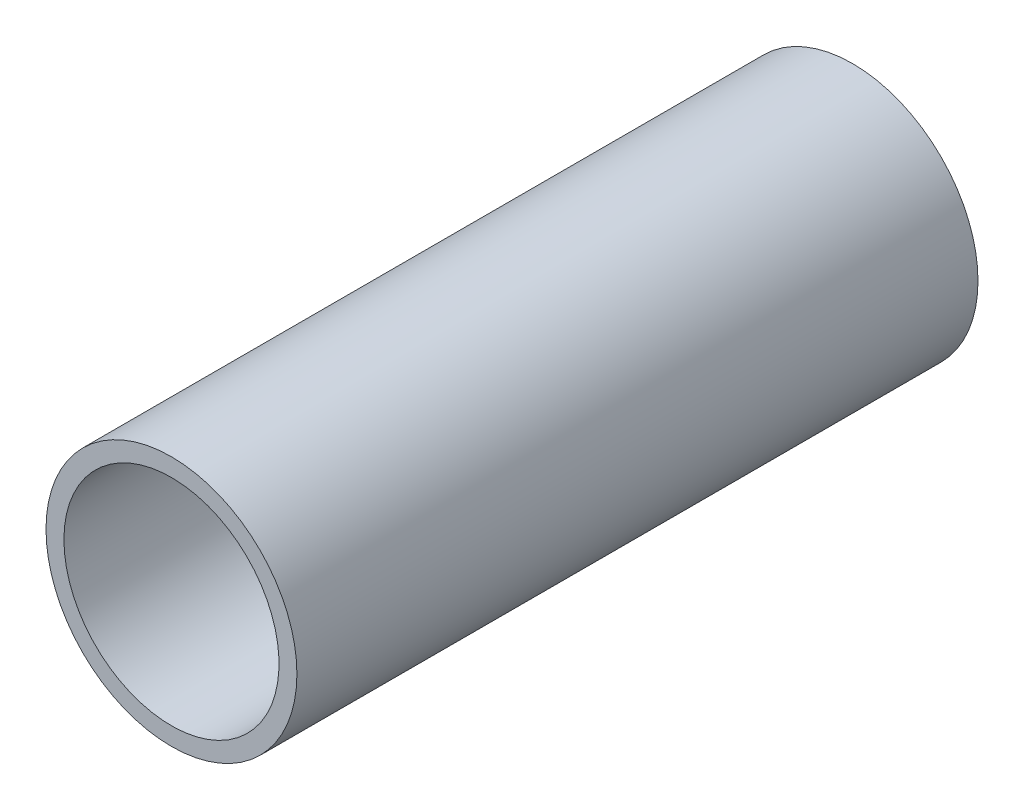
SolidWorks part; units mm, degrees
ref_plane "Front Plane" through (0, 0, 0) normal (0, 0, 1) x (1, 0, 0)
ref_plane "Top Plane" through (0, 0, 0) normal (0, 1, 0) x (1, 0, 0)
ref_plane "Right Plane" through (0, 0, 0) normal (1, 0, 0) x (0, 0, -1)
sketch "Sketch1" plane through (0, 0, 0) normal (0, 0, 1) x (1, 0, 0)
  circle A0 centre (0, 0) radius 5.5562
  circle A1 centre (0, 0) radius 4.7625
  point P5 (0, 0)
  dimension "D1" = 11.1125
  dimension "D2" = 9.525
extrude "Boss-Extrude1" add sketch "Sketch1" along normal blind 30.1625
